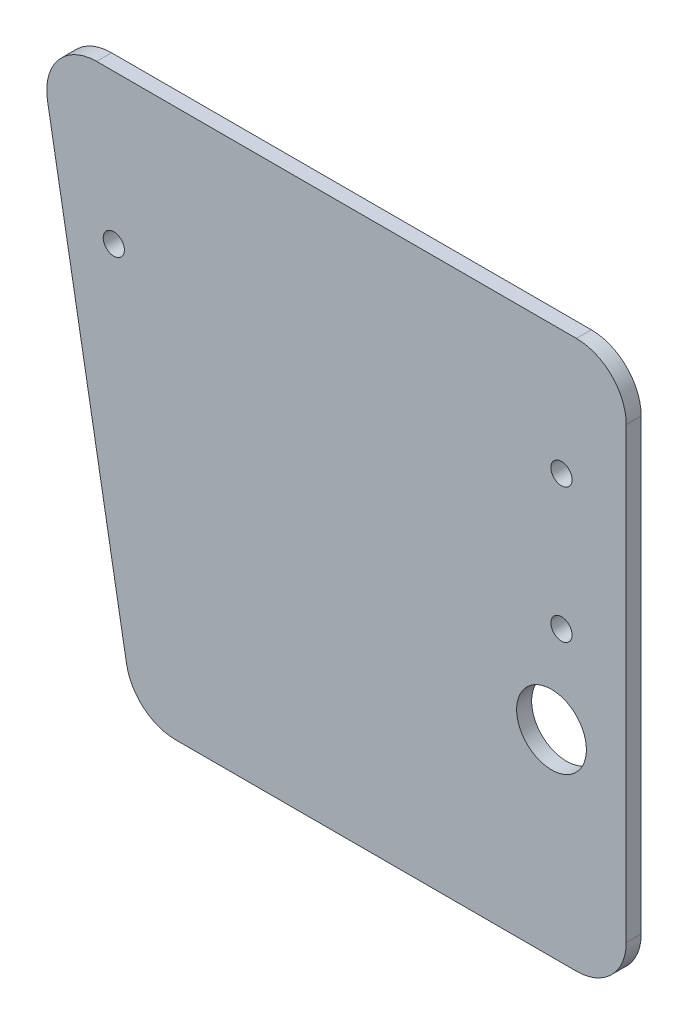
SolidWorks part; units mm, degrees
ref_plane "Front Plane" through (0, 0, 0) normal (0, 0, 1) x (1, 0, 0)
ref_plane "Top Plane" through (0, 0, 0) normal (0, 1, 0) x (1, 0, 0)
ref_plane "Right Plane" through (0, 0, 0) normal (1, 0, 0) x (0, 0, -1)
sketch "Sketch4" plane through (0, 0, 0) normal (0, 0, 1) x (1, 0, 0)
  line L0 (0, 0) -> (118.236, 0)
  line L2 (19.396, -110) -> (0, 0)
  line L3 (19.396, -110) -> (118.236, -110)
  line L4 (118.236, -110) -> (118.236, 0)
  dimension "D1" = 98.84
  dimension "D2" = 100
  dimension "D3" = 110
extrude "Boss-Extrude3" add sketch "Sketch4" along normal blind 3
sketch "Sketch5" plane through (0, 0, 3) normal (0, 0, 1) x (1, 0, 0)
  line L0 (118.236, 0) -> (0, 0) construction
  line L1 (118.236, -110) -> (118.236, 0) construction
  line L2 (19.396, -110) -> (118.236, -110) construction
  circle A0 centre (105.236, -25) radius 2.125
  circle A1 centre (15.375, -30) radius 2.125
  circle A2 centre (103.236, -70.5) radius 7
  dimension "D1" = 4.25
  dimension "D2" = 4.25
  dimension "D7" = 14
  dimension "D3" = 85
  dimension "D4" = 13
  dimension "D5" = 30
  dimension "D6" = 90
  dimension "D8" = 15
  dimension "D9" = 39.5
extrude "Cut-Extrude1" cut sketch "Sketch5" against normal blind 10
fillet "Fillet1" radius 10 4 edges at (118.236, 0, 1.5) (118.236, -110, 1.5) (19.396, -110, 1.5) (0, 0, 1.5)
sketch "Sketch6" plane through (0, 0, 3) normal (0, 0, 1) x (1, 0, 0)
  line L1 (118.236, -100) -> (118.236, -10) construction
  circle A0 centre (105.236, -52) radius 2.125
  circle A3 centre (105.236, -25) radius 2.125 construction
  dimension "D1" = 13
  dimension "D2" = 27
  dimension "D3" = 4.25
extrude "Cut-Extrude2" cut sketch "Sketch6" against normal up to surface (3 mm away) up to face at (103.111, -25, 0)
